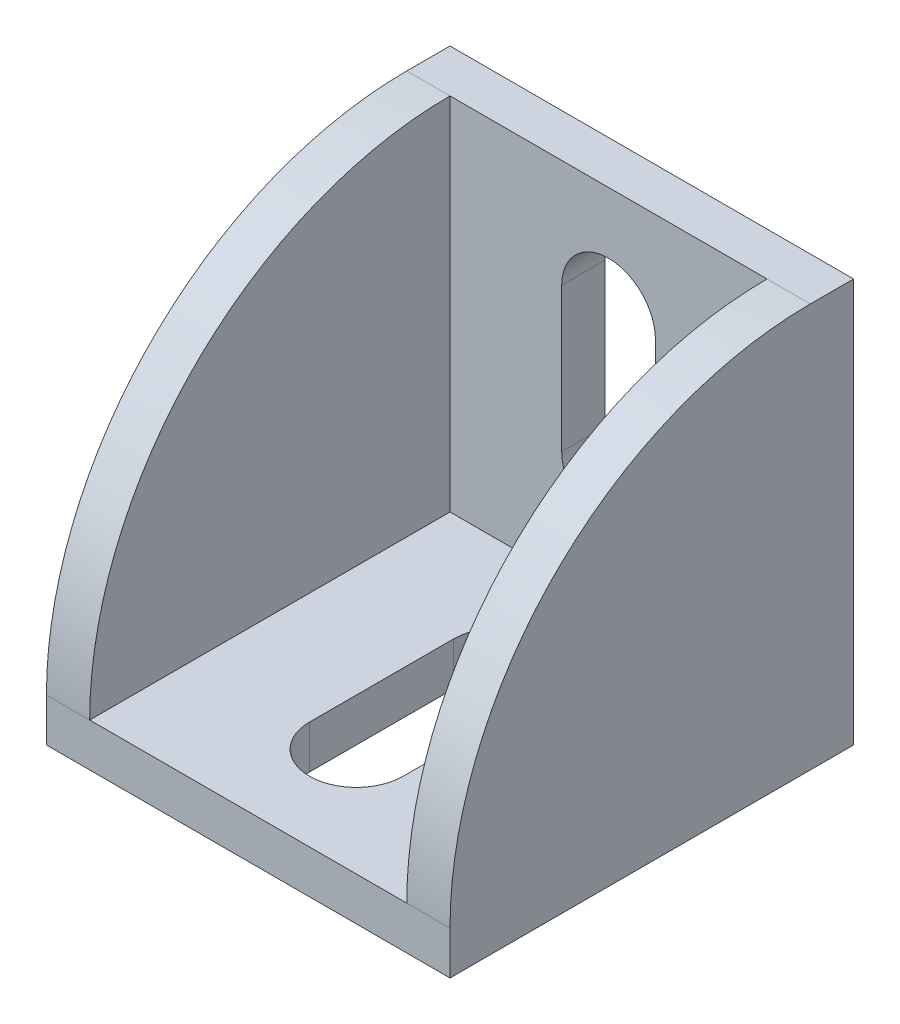
SolidWorks part; units mm, degrees
material "1060 Alloy"
ref_plane "Front Plane" through (0, 0, 0) normal (0, 0, 1) x (1, 0, 0)
ref_plane "Top Plane" through (0, 0, 0) normal (0, 1, 0) x (1, 0, 0)
ref_plane "Right Plane" through (0, 0, 0) normal (1, 0, 0) x (0, 0, -1)
sketch "Sketch1" plane through (0, 0, 0) normal (0, 1, 0) x (1, 0, 0)
  line L0 (0, 0) -> (28, 0)
  line L1 (28, 0) -> (28, -28)
  line L2 (28, -28) -> (0, -28)
  line L3 (0, -28) -> (0, 0)
extrude "Boss-Extrude1" add sketch "Sketch1" along normal blind 3
sketch "Sketch2" plane through (0, 0, 0) normal (0, 0, -1) x (-1, 0, 0)
  line L0 (-28, 3) -> (-28, 28)
  line L1 (-28, 28) -> (0, 28)
  line L2 (0, 28) -> (0, 3)
  line L3 (-28, 3) -> (0, 3) construction
  line L4 (0, 3) -> (-28, 3)
extrude "Boss-Extrude2" add sketch "Sketch2" against normal blind 3
sketch "Sketch3" plane through (0, 0, 0) normal (-1, 0, 0) x (0, 0, 1)
  line L0 (3, 3) -> (28, 3) construction
  line L1 (3, 28) -> (3, 3)
  line L2 (3, 3) -> (28, 3)
  arc A0 (3, 28) -> (28, 3) centre (3, 3) cw
extrude "Boss-Extrude3" add sketch "Sketch3" against normal blind 3
sketch "Sketch4" plane through (28, 0, 0) normal (1, 0, 0) x (0, 0, -1)
  line L0 (-3, 28) -> (-3, 3) construction
  line L1 (-28, 3) -> (-3, 3) construction
  line L2 (-28, 3) -> (-3, 3)
  line L3 (-3, 3) -> (-3, 28)
  arc A0 (-3, 28) -> (-28, 3) centre (-3, 3) ccw
extrude "Boss-Extrude4" add sketch "Sketch4" against normal blind 3
sketch "Sketch5" plane through (0, 0, 3) normal (0, 0, 1) x (1, 0, 0)
  line L0 (14, 28) -> (14, 3) construction
  line L1 (3, 28) -> (25, 28) construction
  line L2 (25, 3) -> (3, 3) construction
  line L3 (3, 15.5) -> (25, 15.5) construction
  line L4 (3, 28) -> (3, 3) construction
  line L5 (25, 3) -> (25, 28) construction
  line L6 (14, 10.5) -> (14, 20.5) construction
  line L7 (10.75, 10.5) -> (10.75, 20.5)
  line L8 (17.25, 10.5) -> (17.25, 20.5)
  arc A0 (10.75, 10.5) -> (17.25, 10.5) centre (14, 10.5) ccw
  arc A1 (17.25, 20.5) -> (10.75, 20.5) centre (14, 20.5) ccw
  point P14 (14, 15.5)
extrude "Cut-Extrude1" cut sketch "Sketch5" against normal blind 3
sketch "Sketch6" plane through (0, 3, 0) normal (0, 1, 0) x (1, 0, 0)
  line L0 (14, -28) -> (14, -3) construction
  line L1 (3, -28) -> (25, -28) construction
  line L2 (25, -3) -> (3, -3) construction
  line L3 (25, -15.5) -> (3, -15.5) construction
  line L4 (25, -28) -> (25, -3) construction
  line L5 (3, -3) -> (3, -28) construction
  line L6 (14, -10.5) -> (14, -20.5) construction
  line L8 (17.25, -10.5) -> (17.25, -20.5)
  line L9 (10.75, -10.5) -> (10.75, -20.5)
  arc A0 (17.25, -10.5) -> (10.75, -10.5) centre (14, -10.5) ccw
  arc A1 (10.75, -20.5) -> (17.25, -20.5) centre (14, -20.5) ccw
  point P16 (14, -15.5)
extrude "Cut-Extrude2" cut sketch "Sketch6" against normal blind 3
